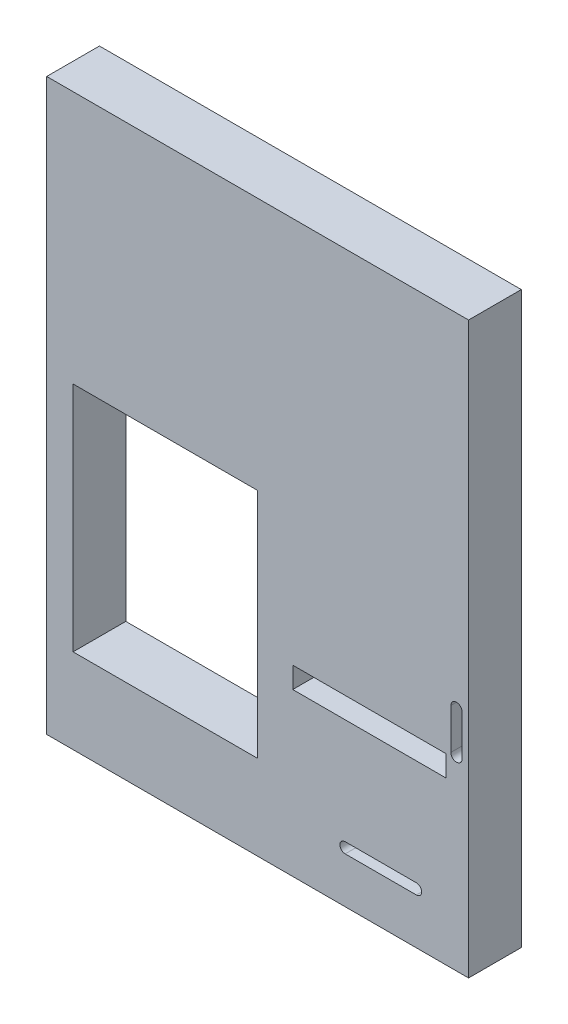
SolidWorks part; units mm, degrees
ref_plane "Front Plane" through (0, 0, 0) normal (0, 0, 1) x (1, 0, 0)
ref_plane "Top Plane" through (0, 0, 0) normal (0, 1, 0) x (1, 0, 0)
ref_plane "Right Plane" through (0, 0, 0) normal (1, 0, 0) x (0, 0, -1)
sketch "Sketch1" plane through (0, 0, 0) normal (0, 0, 1) x (1, 0, 0)
  line L0 (0, -120) -> (87.5104, -120)
  line L1 (100, -120) -> (-100, -120)
  line L2 (100, -120) -> (100, 120)
  line L3 (100, 120) -> (-100, 120)
  line L4 (-100, -120) -> (-100, 120)
  line L7 (0, 0) -> (87.5104, 0)
  line L8 (0, 0) -> (0, -120)
  line L9 (0, -120) -> (87.5104, -120)
  line L10 (87.5104, 0) -> (87.5104, -120)
  point P0 (0, 0)
  dimension "D1" = 240
  dimension "D2" = 200
  dimension "D3" = 87.5104
  dimension "D4" = 120
  dimension "D5" = 100
extrude "Boss-Extrude3" add sketch "Sketch1" along normal blind 25 contours L2 L1 L4 L3
sketch "Sketch3" plane through (0, 0, 25) normal (0, 0, 1) x (1, 0, 0)
  line L5 (-100, -120) -> (-100, 120) construction
  line L6 (0, 0) -> (-87.5, 0)
  line L7 (0, 0) -> (0, -110)
  line L8 (0, -110) -> (-87.5, -110)
  line L9 (-87.5, 0) -> (-87.5, -110)
  line L10 (100, 120) -> (-100, 120) construction
  dimension "D2" = 200
extrude "Cut-Extrude1" cut sketch "Sketch3" against normal blind 25
sketch "Sketch4" plane through (0, 0, 25) normal (0, 0, 1) x (1, 0, 0)
  line L1 (-100, -120) -> (100, -120)
  line L2 (-100, -120) -> (-100, -150.1642)
  line L3 (-100, -150.1642) -> (100, -150.1642)
  line L4 (100, -120) -> (100, -150.1642)
extrude "Boss-Extrude4" add sketch "Sketch4" against normal blind 25
sketch "Sketch8" plane through (0, 0, 0) normal (0, 0, -1) x (-1, 0, 0)
  line L1 (-89.3675, -63.394) -> (-16.6491, -63.394)
  line L2 (-89.3675, -63.394) -> (-89.3675, -73.394)
  line L3 (-89.3675, -73.394) -> (-16.6491, -73.394)
  line L4 (-16.6491, -63.394) -> (-16.6491, -73.394)
  dimension "D1" = 10
sketch "Sketch9" plane through (0, 0, 0) normal (0, 0, -1) x (-1, 0, 0)
  line L0 (-94.2568, -42.4693) -> (-94.2568, -61.7492) construction
  line L1 (-91.5975, -42.4693) -> (-91.5975, -61.7492)
  line L2 (-96.9161, -42.4693) -> (-96.9161, -61.7492)
  arc A0 (-91.5975, -42.4693) -> (-96.9161, -42.4693) centre (-94.2568, -42.4693) ccw
  arc A1 (-96.9161, -61.7492) -> (-91.5975, -61.7492) centre (-94.2568, -61.7492) ccw
  point P2 (-94.2568, -52.1093)
extrude "Cut-Extrude3" cut sketch "Sketch9" against normal blind 40
sketch "Sketch10" plane through (0, 0, 0) normal (0, 0, -1) x (-1, 0, 0)
  line L0 (-75.2671, -125.9455) -> (-41.4919, -125.9455) construction
  line L1 (-75.2671, -123.4455) -> (-41.4919, -123.4455)
  line L2 (-75.2671, -128.4455) -> (-41.4919, -128.4455)
  arc A0 (-75.2671, -123.4455) -> (-75.2671, -128.4455) centre (-75.2671, -125.9455) ccw
  arc A1 (-41.4919, -128.4455) -> (-41.4919, -123.4455) centre (-41.4919, -125.9455) ccw
  point P2 (-58.3795, -125.9455)
  dimension "D1" = 2.5
extrude "Cut-Extrude4" cut sketch "Sketch10" against normal blind 40
extrude "Cut-Extrude5" cut sketch "Sketch8" against normal blind 40
